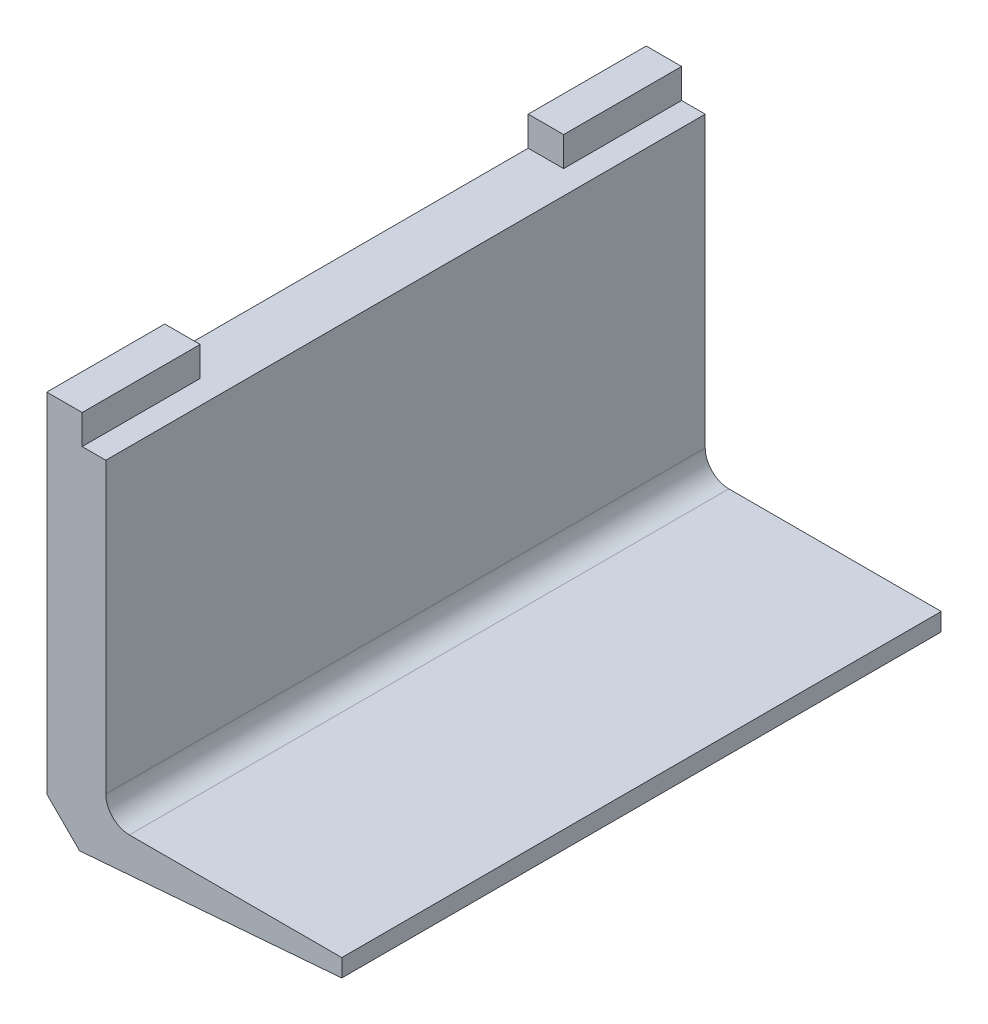
SolidWorks part; units mm, degrees
ref_plane "Front Plane" through (0, 0, 0) normal (0, 0, 1) x (1, 0, 0)
ref_plane "Top Plane" through (0, 0, 0) normal (0, 1, 0) x (1, 0, 0)
ref_plane "Right Plane" through (0, 0, 0) normal (1, 0, 0) x (0, 0, -1)
sketch "Sketch1" plane through (0, 0, 0) normal (0, 0, 1) x (1, 0, 0)
  line L0 (-33.4127, -41.5732) -> (16.5873, -37.5732)
  line L1 (-33.4127, 18.4268) -> (-23.4127, 18.4268)
  line L2 (-33.4127, 18.4268) -> (-33.4127, -33.5732)
  line L4 (-23.4127, 18.4268) -> (-23.4127, -34.5732)
  line L5 (-23.4127, -34.5732) -> (16.5873, -34.5732)
  line L6 (-33.4127, -33.5732) -> (-33.4127, -41.5732)
  line L8 (16.5873, -34.5732) -> (16.5873, -37.5732)
  dimension "D1" = 10
  dimension "D2" = 53
extrude "Boss-Extrude1" add sketch "Sketch1" along normal blind 101.6
chamfer "Chamfer1" distance 6 angle 45 1 edges at (-33.4127, -41.5732, 50.8)
fillet "Fillet1" radius 4 1 edges at (-23.4127, -34.5732, 50.8)
sketch "Sketch2" plane through (0, 18.4268, 0) normal (0, 1, 0) x (1, 0, 0)
  line L1 (-33.4127, -101.6) -> (-27.4127, -101.6)
  line L2 (-33.4127, -101.6) -> (-33.4127, -81.6)
  line L3 (-33.4127, -81.6) -> (-27.4127, -81.6)
  line L4 (-27.4127, -101.6) -> (-27.4127, -81.6)
  line L5 (-33.4127, 0) -> (-27.4127, 0)
  line L6 (-33.4127, 0) -> (-33.4127, -20)
  line L7 (-33.4127, -20) -> (-27.4127, -20)
  line L8 (-27.4127, 0) -> (-27.4127, -20)
  dimension "D1" = 6
  dimension "D2" = 6
  dimension "D3" = 20
  dimension "D4" = 20
extrude "Boss-Extrude2" add sketch "Sketch2" along normal blind 5
